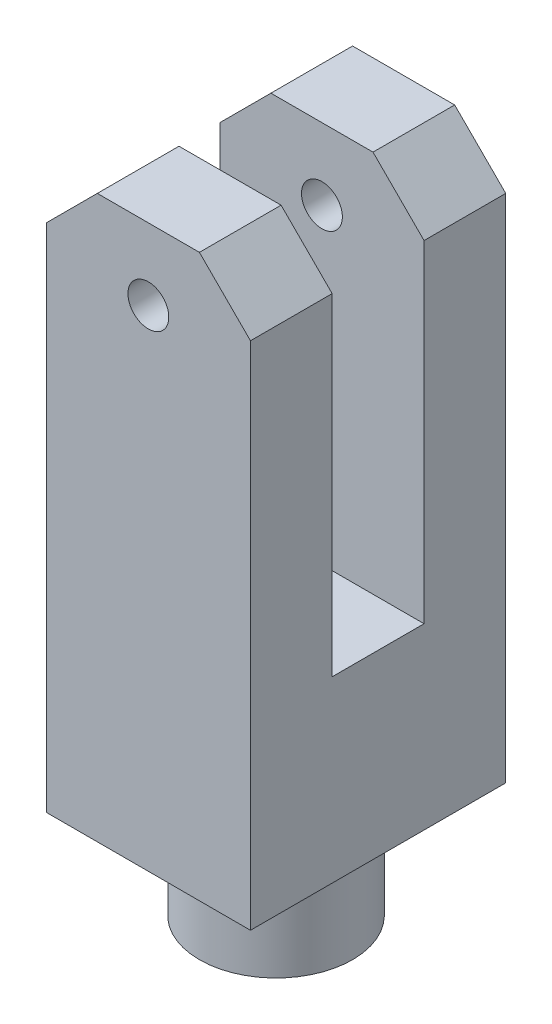
SolidWorks part; units mm, degrees
ref_plane "Front Plane" through (0, 0, 0) normal (0, 0, 1) x (1, 0, 0)
ref_plane "Top Plane" through (0, 0, 0) normal (0, 1, 0) x (1, 0, 0)
ref_plane "Right Plane" through (0, 0, 0) normal (1, 0, 0) x (0, 0, -1)
sketch "Sketch1" plane through (0, 0, 0) normal (0, 1, 0) x (1, 0, 0)
  circle A0 centre (0, 0) radius 15
extrude "Boss-Extrude1" add sketch "Sketch1" along normal blind 20
sketch "Sketch2" plane through (0, 20, 0) normal (0, 1, 0) x (1, 0, 0)
  line L1 (-20, 25) -> (20, 25)
  line L2 (-20, 25) -> (-20, -25)
  line L3 (-20, -25) -> (20, -25)
  line L4 (20, 25) -> (20, -25)
  line L5 (-20, 25) -> (20, -25) construction
  line L6 (-20, -25) -> (20, 25) construction
  point P0 (0, 0)
extrude "Boss-Extrude2" add sketch "Sketch2" along normal blind 110
sketch "Sketch3" plane through (20, 0, 0) normal (1, 0, 0) x (0, 0, -1)
  line L0 (-25, 130) -> (25, 130) construction
  line L1 (-9, 205) -> (9, 205)
  line L2 (-9, 205) -> (-9, 55)
  line L3 (-9, 55) -> (9, 55)
  line L4 (9, 205) -> (9, 55)
  line L5 (-9, 205) -> (9, 55) construction
  line L6 (-9, 55) -> (9, 205) construction
  point P0 (0, 130)
extrude "Cut-Extrude1" cut sketch "Sketch3" against normal through all
sketch "Sketch4" plane through (0, 0, -25) normal (0, 0, -1) x (-1, 0, 0)
  line L0 (-20, 20) -> (20, 20) construction
  circle A0 centre (0, 116) radius 4
  dimension "D1" = 96
extrude "Cut-Extrude2" cut sketch "Sketch4" against normal through all
chamfer "Chamfer1" distance 10 angle 45 4 edges at (-20, 130, 17) (-20, 130, -17) (20, 130, -17) (20, 130, 17)
